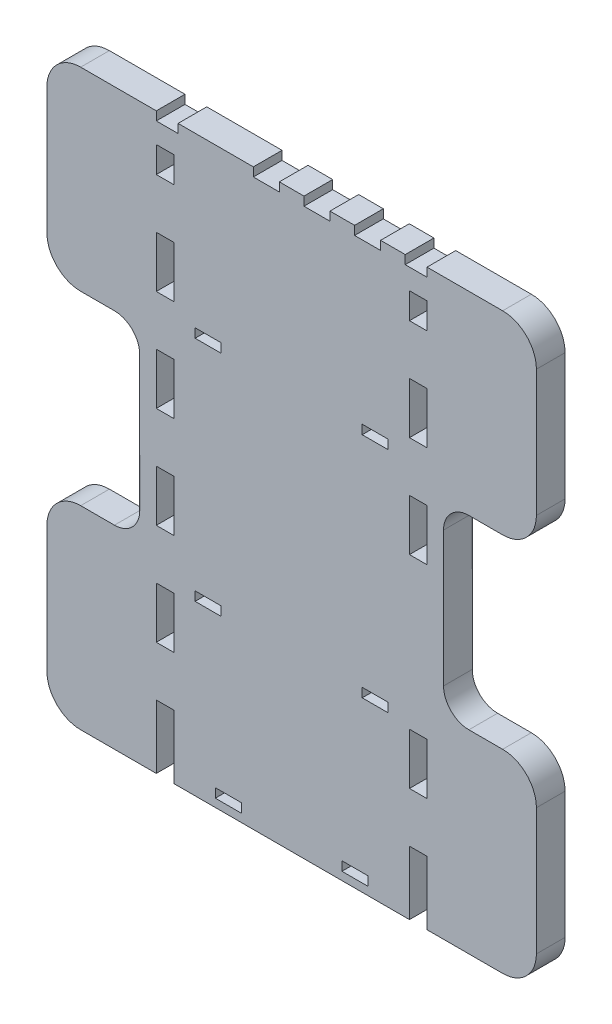
SolidWorks part; units mm, degrees
ref_plane "Front Plane" through (0, 0, 0) normal (0, 0, 1) x (1, 0, 0)
ref_plane "Top Plane" through (0, 0, 0) normal (0, 1, 0) x (1, 0, 0)
ref_plane "Right Plane" through (0, 0, 0) normal (1, 0, 0) x (0, 0, -1)
sketch "Model" plane through (0, 0, 0) normal (0, 0, 1) x (1, 0, 0)
  line L111 (-144.1781, -108.3192) -> (-99.3781, -108.3192)
  line L112 (-99.3781, -108.3192) -> (-99.3781, -70.6192)
  line L113 (-99.3781, -70.6192) -> (-88.9781, -70.6192)
  line L114 (-88.9781, -70.6192) -> (-88.9781, -108.3192)
  line L115 (-88.9781, -108.3192) -> (50.6219, -108.3192)
  line L116 (50.6219, -108.3192) -> (50.6219, -70.6192)
  line L117 (50.6219, -70.6192) -> (61.0219, -70.6192)
  line L118 (61.0219, -70.6192) -> (61.0219, -108.3192)
  line L119 (61.0219, -108.3192) -> (105.8219, -108.3192)
  line L120 (125.8219, -88.3192) -> (125.8219, -13.3192)
  line L121 (105.8219, 6.6808) -> (85.8219, 6.6808)
  line L122 (70.8219, 21.6808) -> (70.8219, 101.6808)
  line L123 (85.8219, 116.6808) -> (105.8219, 116.6808)
  line L124 (125.8219, 136.6808) -> (125.8219, 211.6808)
  line L125 (105.8219, 231.6808) -> (61.0219, 231.6808)
  line L126 (61.0219, 231.6808) -> (61.0219, 226.4808)
  line L127 (61.0219, 226.4808) -> (48.1219, 226.4808)
  line L128 (48.1219, 226.4808) -> (48.1219, 231.6808)
  line L129 (48.1219, 231.6808) -> (33.5219, 231.6808)
  line L130 (33.5219, 231.6808) -> (33.5219, 226.4808)
  line L131 (33.5219, 226.4808) -> (18.1219, 226.4808)
  line L132 (18.1219, 226.4808) -> (18.1219, 231.6808)
  line L133 (18.1219, 231.6808) -> (3.5219, 231.6808)
  line L134 (3.5219, 231.6808) -> (3.5219, 226.4808)
  line L135 (3.5219, 226.4808) -> (-11.8781, 226.4808)
  line L136 (-11.8781, 226.4808) -> (-11.8781, 231.6808)
  line L137 (-11.8781, 231.6808) -> (-26.4781, 231.6808)
  line L138 (-26.4781, 231.6808) -> (-26.4781, 226.4808)
  line L139 (-26.4781, 226.4808) -> (-41.8781, 226.4808)
  line L140 (-41.8781, 226.4808) -> (-41.8781, 231.6808)
  line L141 (-41.8781, 231.6808) -> (-86.4781, 231.6808)
  line L142 (-86.4781, 231.6808) -> (-86.4781, 226.4808)
  line L143 (-86.4781, 226.4808) -> (-99.3781, 226.4808)
  line L144 (-99.3781, 226.4808) -> (-99.3781, 231.6808)
  line L145 (-99.3781, 231.6808) -> (-144.1781, 231.6808)
  line L146 (-164.1781, 211.6808) -> (-164.1781, 136.6808)
  line L147 (-144.1781, 116.6808) -> (-124.1781, 116.6808)
  line L148 (-109.1781, 101.6808) -> (-109.1781, 21.6808)
  line L149 (-124.1781, 6.6808) -> (-144.1781, 6.6808)
  line L150 (-164.1781, -13.3192) -> (-164.1781, -88.3192)
  line L151 (22.6219, 131.8808) -> (38.0219, 131.8808)
  line L152 (38.0219, 131.8808) -> (38.0219, 126.4808)
  line L153 (38.0219, 126.4808) -> (22.6219, 126.4808)
  line L154 (22.6219, 126.4808) -> (22.6219, 131.8808)
  line L155 (-60.9781, 126.4808) -> (-76.3781, 126.4808)
  line L156 (-76.3781, 126.4808) -> (-76.3781, 131.8808)
  line L157 (-76.3781, 131.8808) -> (-60.9781, 131.8808)
  line L158 (-60.9781, 131.8808) -> (-60.9781, 126.4808)
  line L159 (22.6219, -3.1192) -> (38.0219, -3.1192)
  line L160 (38.0219, -3.1192) -> (38.0219, -8.5192)
  line L161 (38.0219, -8.5192) -> (22.6219, -8.5192)
  line L162 (22.6219, -8.5192) -> (22.6219, -3.1192)
  line L163 (-60.9781, -8.5192) -> (-76.3781, -8.5192)
  line L164 (-76.3781, -8.5192) -> (-76.3781, -3.1192)
  line L165 (-76.3781, -3.1192) -> (-60.9781, -3.1192)
  line L166 (-60.9781, -3.1192) -> (-60.9781, -8.5192)
  line L167 (-99.3781, 198.9808) -> (-99.3781, 214.3808)
  line L168 (-99.3781, 214.3808) -> (-88.9781, 214.3808)
  line L169 (-88.9781, 214.3808) -> (-88.9781, 198.9808)
  line L170 (-88.9781, 198.9808) -> (-99.3781, 198.9808)
  line L171 (-99.3781, -10.6192) -> (-88.9781, -10.6192)
  line L172 (-88.9781, -10.6192) -> (-88.9781, -41.0192)
  line L173 (-88.9781, -41.0192) -> (-99.3781, -41.0192)
  line L174 (-99.3781, -41.0192) -> (-99.3781, -10.6192)
  line L175 (-99.3781, 78.9808) -> (-99.3781, 109.3808)
  line L176 (-99.3781, 109.3808) -> (-88.9781, 109.3808)
  line L177 (-88.9781, 109.3808) -> (-88.9781, 78.9808)
  line L178 (-88.9781, 78.9808) -> (-99.3781, 78.9808)
  line L179 (-99.3781, 169.3808) -> (-88.9781, 169.3808)
  line L180 (-88.9781, 169.3808) -> (-88.9781, 138.9808)
  line L181 (-88.9781, 138.9808) -> (-99.3781, 138.9808)
  line L182 (-99.3781, 138.9808) -> (-99.3781, 169.3808)
  line L183 (61.0219, -41.0192) -> (50.6219, -41.0192)
  line L184 (50.6219, -41.0192) -> (50.6219, -10.6192)
  line L185 (50.6219, -10.6192) -> (61.0219, -10.6192)
  line L186 (61.0219, -10.6192) -> (61.0219, -41.0192)
  line L187 (61.0219, 78.9808) -> (50.6219, 78.9808)
  line L188 (50.6219, 78.9808) -> (50.6219, 109.3808)
  line L189 (50.6219, 109.3808) -> (61.0219, 109.3808)
  line L190 (61.0219, 109.3808) -> (61.0219, 78.9808)
  line L191 (61.0219, 138.9808) -> (50.6219, 138.9808)
  line L192 (50.6219, 138.9808) -> (50.6219, 169.3808)
  line L193 (50.6219, 169.3808) -> (61.0219, 169.3808)
  line L194 (61.0219, 169.3808) -> (61.0219, 138.9808)
  line L195 (10.6219, -103.5192) -> (10.6219, -98.1192)
  line L196 (10.6219, -98.1192) -> (26.0219, -98.1192)
  line L197 (26.0219, -98.1192) -> (26.0219, -103.5192)
  line L198 (26.0219, -103.5192) -> (10.6219, -103.5192)
  line L199 (-64.3781, -103.5192) -> (-64.3781, -98.1192)
  line L200 (-64.3781, -98.1192) -> (-48.9781, -98.1192)
  line L201 (-48.9781, -98.1192) -> (-48.9781, -103.5192)
  line L202 (-48.9781, -103.5192) -> (-64.3781, -103.5192)
  line L203 (61.0219, 198.9808) -> (50.6219, 198.9808)
  line L204 (50.6219, 198.9808) -> (50.6219, 214.3808)
  line L205 (50.6219, 214.3808) -> (61.0219, 214.3808)
  line L206 (61.0219, 214.3808) -> (61.0219, 198.9808)
  line L207 (-88.9781, 49.3808) -> (-88.9781, 18.9808)
  line L208 (-88.9781, 18.9808) -> (-99.3781, 18.9808)
  line L209 (-99.3781, 18.9808) -> (-99.3781, 49.3808)
  line L210 (-99.3781, 49.3808) -> (-88.9781, 49.3808)
  arc A7 (-164.1781, -88.3192) -> (-144.1781, -108.3192) centre (-144.1781, -88.3192) ccw
  arc A8 (105.8219, -108.3192) -> (125.8219, -88.3192) centre (105.8219, -88.3192) ccw
  arc A9 (125.8219, -13.3192) -> (105.8219, 6.6808) centre (105.8219, -13.3192) ccw
  arc A10 (70.8219, 21.6808) -> (85.8219, 6.6808) centre (85.8219, 21.6808) ccw
  arc A11 (85.8219, 116.6808) -> (70.8219, 101.6808) centre (85.8219, 101.6808) ccw
  arc A12 (105.8219, 116.6808) -> (125.8219, 136.6808) centre (105.8219, 136.6808) ccw
  arc A13 (125.8219, 211.6808) -> (105.8219, 231.6808) centre (105.8219, 211.6808) ccw
  arc A14 (-144.1781, 231.6808) -> (-164.1781, 211.6808) centre (-144.1781, 211.6808) ccw
  arc A15 (-164.1781, 136.6808) -> (-144.1781, 116.6808) centre (-144.1781, 136.6808) ccw
  arc A16 (-109.1781, 101.6808) -> (-124.1781, 116.6808) centre (-124.1781, 101.6808) ccw
  arc A17 (-124.1781, 6.6808) -> (-109.1781, 21.6808) centre (-124.1781, 21.6808) ccw
  arc A18 (-144.1781, 6.6808) -> (-164.1781, -13.3192) centre (-144.1781, -13.3192) ccw
extrude "Boss-Extrude1" add sketch "Model" along normal blind 17
